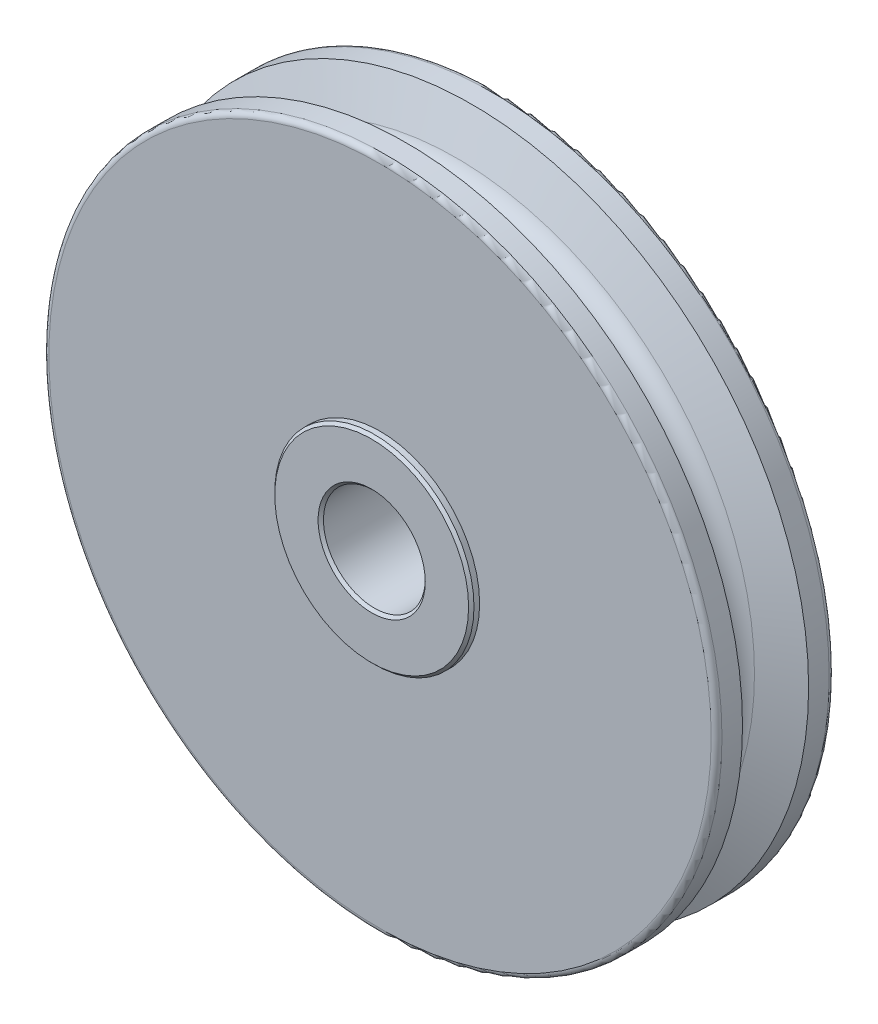
SolidWorks part; units mm, degrees
ref_plane "Front Plane" through (0, 0, 0) normal (0, 0, 1) x (1, 0, 0)
ref_plane "Top Plane" through (0, 0, 0) normal (0, 1, 0) x (1, 0, 0)
ref_plane "Right Plane" through (0, 0, 0) normal (1, 0, 0) x (0, 0, -1)
sketch "Sketch1" plane through (0, 0, 0) normal (1, 0, 0) x (0, 0, -1)
  line L0 (-3.175, 0) -> (3.175, 0) construction
  line L1 (0, -13.5001) -> (0, 13.5001) construction
  line L2 (-3.175, 2.4003) -> (3.175, 2.4003)
  line L3 (3.175, 2.4003) -> (3.175, 4.699)
  line L4 (3.175, 4.699) -> (-3.175, 4.699)
  line L5 (-3.175, 4.699) -> (-3.175, 2.4003)
  line L6 (-2.7813, 4.699) -> (-2.7813, 15.875)
  line L7 (-2.7813, 15.875) -> (-1.5592, 15.875)
  line L8 (-1.5592, 15.875) -> (-0.8243, 14.0561)
  line L9 (1.5592, 15.875) -> (0.8243, 14.0561)
  line L10 (2.7813, 15.875) -> (1.5592, 15.875)
  line L11 (2.7813, 4.699) -> (2.7813, 15.875)
  line L12 (-2.7813, 15.875) -> (2.7813, 15.875) construction
  arc A0 (-0.8243, 14.0561) -> (0.8243, 14.0561) centre (0, 14.3891) ccw
  point P4 (0, 0)
  point P8 (0, 0)
  dimension "D1" = 44
  dimension "Pulley Radius (R)" = 0.889
  dimension "Bushing Width (D)" = 6.35
  dimension "Bushing ID (A)" = 4.8006
  dimension "Pulley Diameter (B)" = 27.0002
  dimension "Outside Diameter (C)" = 31.75
  dimension "Sheave Width (E)" = 5.5626
  dimension "Bushing OD" = 9.398
sketch "Sketch2" plane through (0, 0, 0) normal (1, 0, 0) x (0, 0, -1)
  line L0 (-3.175, 4.699) -> (-3.048, 4.699) construction
  line L1 (3.175, 4.699) -> (-3.175, 4.699) construction
  line L2 (-3.175, 4.699) -> (-3.175, 4.572) construction
  line L3 (-3.175, 4.699) -> (-3.175, 2.4003) construction
  line L4 (-3.175, 2.4003) -> (-3.175, 2.5273) construction
  line L5 (-3.175, 2.4003) -> (-3.048, 2.4003) construction
  line L6 (-3.175, 2.4003) -> (3.175, 2.4003) construction
  line L7 (3.048, 4.699) -> (3.175, 4.699) construction
  line L8 (3.175, 4.699) -> (3.175, 4.572) construction
  line L9 (3.175, 2.4003) -> (3.175, 4.699) construction
  line L10 (3.048, 2.4003) -> (3.175, 2.4003) construction
  line L11 (3.175, 2.4003) -> (3.175, 2.5273) construction
  line L12 (-3.175, 4.572) -> (-3.175, 2.5273)
  line L13 (-3.175, 2.5273) -> (-3.048, 2.4003)
  line L14 (-3.048, 2.4003) -> (3.048, 2.4003)
  line L15 (3.048, 2.4003) -> (3.175, 2.5273)
  line L16 (3.175, 2.5273) -> (3.175, 4.572)
  line L17 (3.175, 4.572) -> (3.048, 4.699)
  line L18 (3.048, 4.699) -> (-3.048, 4.699)
  line L19 (-3.048, 4.699) -> (-3.175, 4.572)
  dimension "D1" = 0.127
revolve "Bushing Revolve" add sketch "Sketch2" angle 360 about L0
sketch "Sketch3" plane through (0, 0, 0) normal (1, 0, 0) x (0, 0, -1)
  line L0 (-2.7813, 4.699) -> (-2.7813, 15.875) construction
  line L1 (-2.7813, 15.875) -> (-1.5592, 15.875) construction
  line L2 (-1.5592, 15.875) -> (-0.8243, 14.0561) construction
  line L3 (1.5592, 15.875) -> (0.8243, 14.0561) construction
  line L4 (-3.175, 2.4003) -> (3.175, 2.4003)
  line L5 (3.175, 2.4003) -> (3.175, 4.699)
  line L6 (3.175, 4.699) -> (-3.175, 4.699)
  line L7 (-3.175, 4.699) -> (-3.175, 2.4003)
  line L10 (2.7813, 4.699) -> (-2.7813, 4.699)
  line L12 (2.7813, 15.875) -> (1.5592, 15.875) construction
  line L13 (2.7813, 4.699) -> (2.7813, 15.875) construction
  line L14 (-2.7813, 4.699) -> (-2.7813, 15.621)
  line L15 (-2.5273, 15.875) -> (-1.5592, 15.875)
  line L16 (-1.5592, 15.875) -> (-0.8243, 14.0561)
  line L17 (1.5592, 15.875) -> (0.8243, 14.0561)
  line L18 (2.5273, 15.875) -> (1.5592, 15.875)
  line L19 (2.7813, 4.699) -> (2.7813, 15.621)
  arc A0 (-0.8243, 14.0561) -> (0.8243, 14.0561) centre (0, 14.3891) ccw construction
  arc A1 (-0.8243, 14.0561) -> (0.8243, 14.0561) centre (0, 14.3891) ccw
  arc A2 (-2.7813, 15.621) -> (-2.5273, 15.875) centre (-2.5273, 15.621) cw
  arc A3 (2.5273, 15.875) -> (2.7813, 15.621) centre (2.5273, 15.621) cw
  dimension "D2" = 0.254
  dimension "D1" = 0
revolve "Sheave Revolve" add sketch "Sketch3" angle 360 about L0
